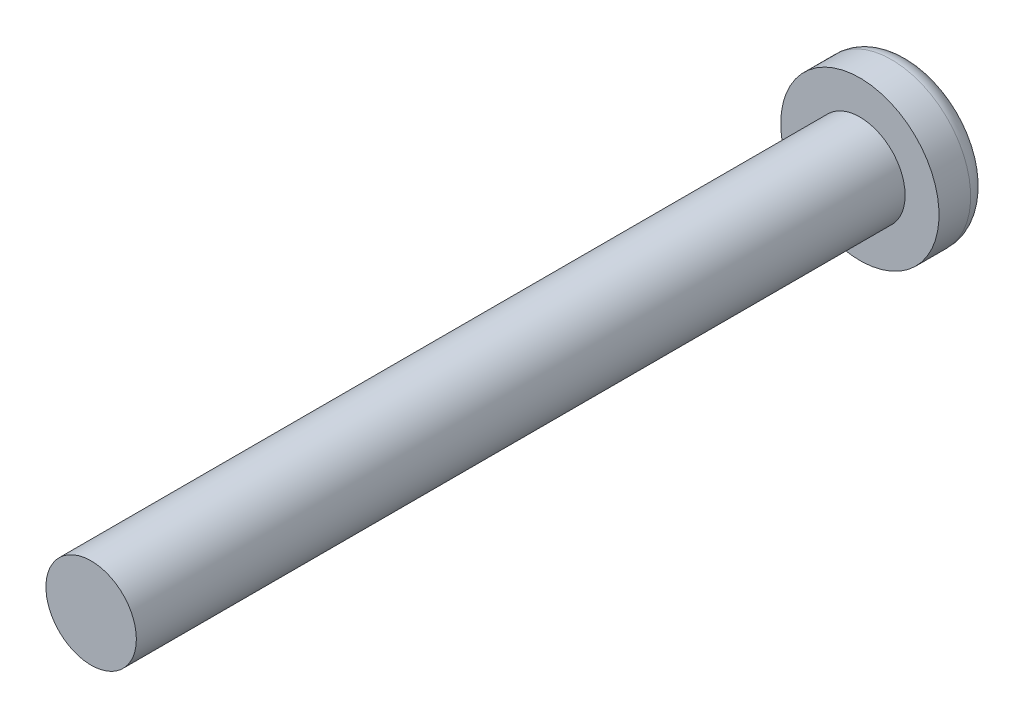
SolidWorks part; units mm, degrees
ref_plane "前视基准面" through (0, 0, 0) normal (0, 0, 1) x (1, 0, 0)
ref_plane "上视基准面" through (0, 0, 0) normal (0, 1, 0) x (1, 0, 0)
ref_plane "右视基准面" through (0, 0, 0) normal (1, 0, 0) x (0, 0, -1)
sketch "草图1" plane through (0, 0, 0) normal (0, 0, 1) x (1, 0, 0)
  circle A0 centre (0, 0) radius 5
extrude "凸台-拉伸1" add sketch "草图1" along normal blind 85 contours A0
sketch "草图2" plane through (0, 0, 0) normal (0, 0, -1) x (-1, 0, 0)
  circle A0 centre (0, 0) radius 8.75
  dimension "D1" = 17.5
extrude "凸台-拉伸2" add sketch "草图2" along normal blind 5.5
fillet "圆角2" radius 2 1 edges at (-8.75, 0, -5.5)
thread "螺纹线1" pitch 0.9071 start angle 0, offset 0, length 0, pitch 0.9071, diameter 10
ref_plane "基准面1" through (5, 0, 0) normal (0, -1, 0) x (1, 0, 0)
sketch "螺纹线轮廓1" plane through (5, 0, 0) normal (0, -1, 0) x (1, 0, 0)
  line L0 (0, 0) -> (0, 0.9071) construction
  line L11 (0, 0) -> (0, 0.7937)
  line L12 (0, 0.7937) -> (-0.491, 0.5103)
  line L13 (-0.491, 0.5103) -> (-0.491, 0.2835)
  line L15 (-0.491, 0.2835) -> (0, 0)
  line L17 (-0.491, 0.3969) -> (0, 0.3969) construction
  point P2 (0, 0)
  dimension "Pitch" = 0.9071
  dimension "Profile_Angle" = 60
  dimension "Profile_Land" = 0.2268
  dimension "Profile_Height" = 0.491
